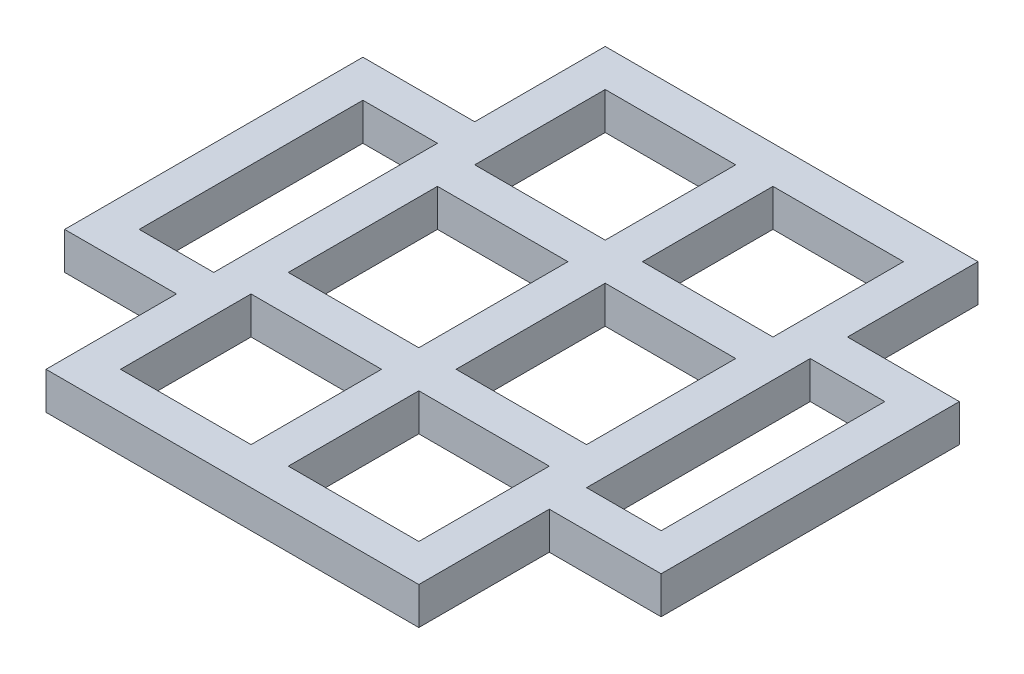
SolidWorks part; units mm, degrees
ref_plane "Front Plane" through (0, 0, 0) normal (0, 0, 1) x (1, 0, 0)
ref_plane "Top Plane" through (0, 0, 0) normal (0, 1, 0) x (1, 0, 0)
ref_plane "Right Plane" through (0, 0, 0) normal (1, 0, 0) x (0, 0, -1)
sketch "Sketch4" plane through (0, 0, 0) normal (0, 1, 0) x (1, 0, 0)
  line L0 (-100, 150) -> (100, 150)
  line L2 (100, -150) -> (-100, -150)
  line L4 (-80, 130) -> (-10, 130)
  line L5 (-10, 130) -> (-10, 60)
  line L6 (-10, 60) -> (-80, 60)
  line L7 (-80, 60) -> (-80, 130)
  line L8 (10, 130) -> (80, 130)
  line L9 (80, 130) -> (80, 60)
  line L10 (80, 60) -> (10, 60)
  line L11 (10, 130) -> (10, 60)
  line L12 (-80, 40) -> (-10, 40)
  line L13 (-10, 40) -> (-10, -40)
  line L14 (-10, -40) -> (-80, -40)
  line L15 (-80, -40) -> (-80, 40)
  line L16 (10, 40) -> (80, 40)
  line L17 (80, 40) -> (80, -40)
  line L18 (80, -40) -> (10, -40)
  line L19 (10, -40) -> (10, 40)
  line L20 (-80, -60) -> (-10, -60)
  line L21 (-10, -60) -> (-10, -130)
  line L22 (-10, -130) -> (-80, -130)
  line L23 (-80, -130) -> (-80, -60)
  line L24 (10, -60) -> (80, -60)
  line L25 (80, -60) -> (80, -130)
  line L26 (80, -130) -> (10, -130)
  line L27 (10, -130) -> (10, -60)
  line L28 (100, 60) -> (140, 60)
  line L29 (140, 60) -> (140, -60)
  line L30 (140, -60) -> (100, -60)
  line L31 (-100, 60) -> (-140, 60)
  line L32 (-140, 60) -> (-140, -60)
  line L33 (-140, -60) -> (-100, -60)
  line L34 (100, 80) -> (160, 80)
  line L35 (160, 80) -> (160, -80)
  line L36 (160, -80) -> (100, -80)
  line L37 (-160, 80) -> (-160, -80)
  line L38 (-160, -80) -> (-100, -80)
  line L39 (-160, 80) -> (-100, 80)
  line L44 (-100, 150) -> (-100, 80)
  line L45 (-100, 60) -> (-100, -60)
  line L46 (-100, -80) -> (-100, -150)
  line L47 (100, -150) -> (100, -80)
  line L48 (100, -60) -> (100, 60)
  line L49 (100, 80) -> (100, 150)
  point P13 (-45, 130)
  point P25 (-80, -95)
  point P46 (-120, -60)
  point P47 (120, 60)
  point P50 (-130, -80)
  dimension "D1" = 300
  dimension "D3" = 150
  dimension "D5" = 20
  dimension "D7" = 20
  dimension "D9" = 70
  dimension "D10" = 70
  dimension "D11" = 70
  dimension "D12" = 70
  dimension "D13" = 20
  dimension "D14" = 80
  dimension "D15" = 70
  dimension "D18" = 70
  dimension "D19" = 80
  dimension "D21" = 70
  dimension "D22" = 20
  dimension "D23" = 70
  dimension "D24" = 20
  dimension "D26" = 70
  dimension "D27" = 20
  dimension "D28" = 120
  dimension "D29" = 60
  dimension "D32" = 20
  dimension "D33" = 20
  dimension "D34" = 20
  dimension "D35" = 20
  dimension "D36" = 20
  dimension "D37" = 20
  dimension "D38" = 20
  dimension "D39" = 60
extrude "Boss-Extrude2" add sketch "Sketch4" along normal blind 20
